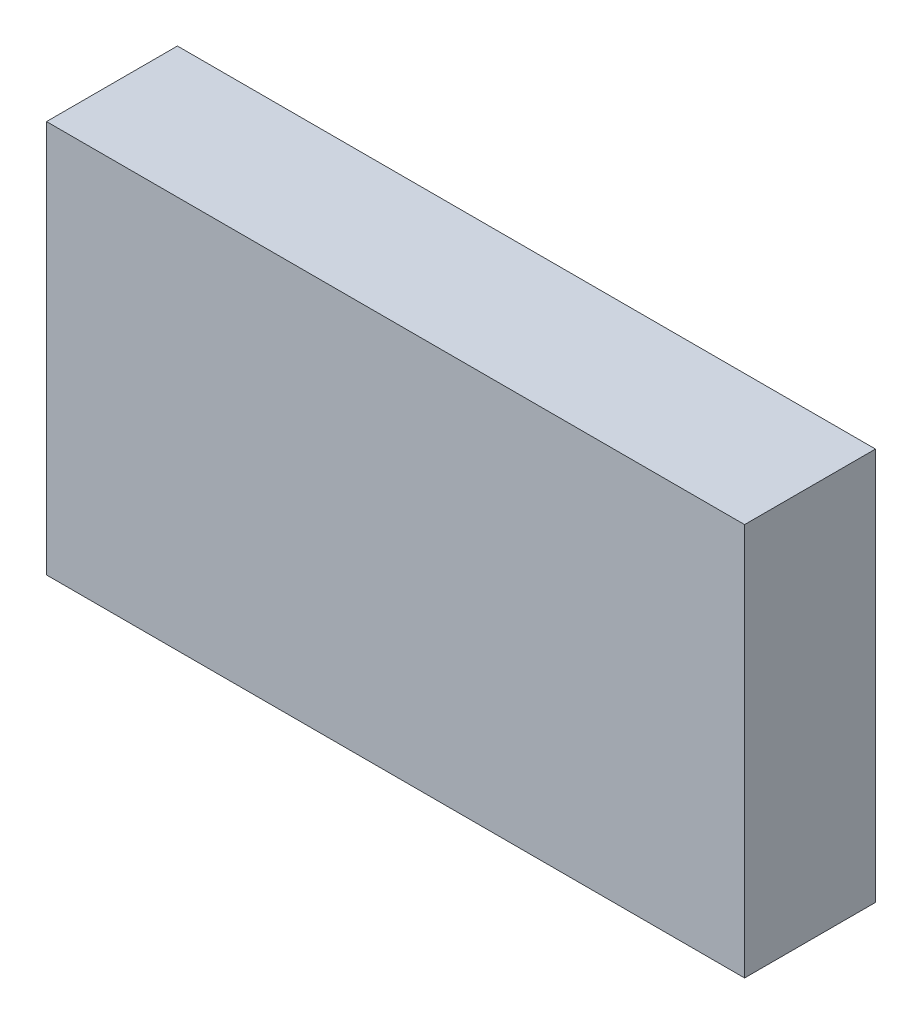
SolidWorks part; units mm, degrees
ref_plane "前视基准面" through (0, 0, 0) normal (0, 0, 1) x (1, 0, 0)
ref_plane "上视基准面" through (0, 0, 0) normal (0, 1, 0) x (1, 0, 0)
ref_plane "右视基准面" through (0, 0, 0) normal (1, 0, 0) x (0, 0, -1)
sketch "草图1" plane through (0, 0, 0) normal (0, 0, 1) x (1, 0, 0)
  line L1 (0, 0) -> (-160, 0)
  line L2 (0, 0) -> (0, 90)
  line L3 (0, 90) -> (-160, 90)
  line L4 (-160, 0) -> (-160, 90)
  dimension "D1" = 90
  dimension "D2" = 160
extrude "凸台-拉伸1" add sketch "草图1" along normal blind 30
sketch "草图3" plane through (0, 0, 0) normal (0, 0, -1) x (-1, 0, 0)
  text T0 "POWER BANK"
extrude "切除-拉伸1" cut sketch "草图3" against normal blind 0.5
